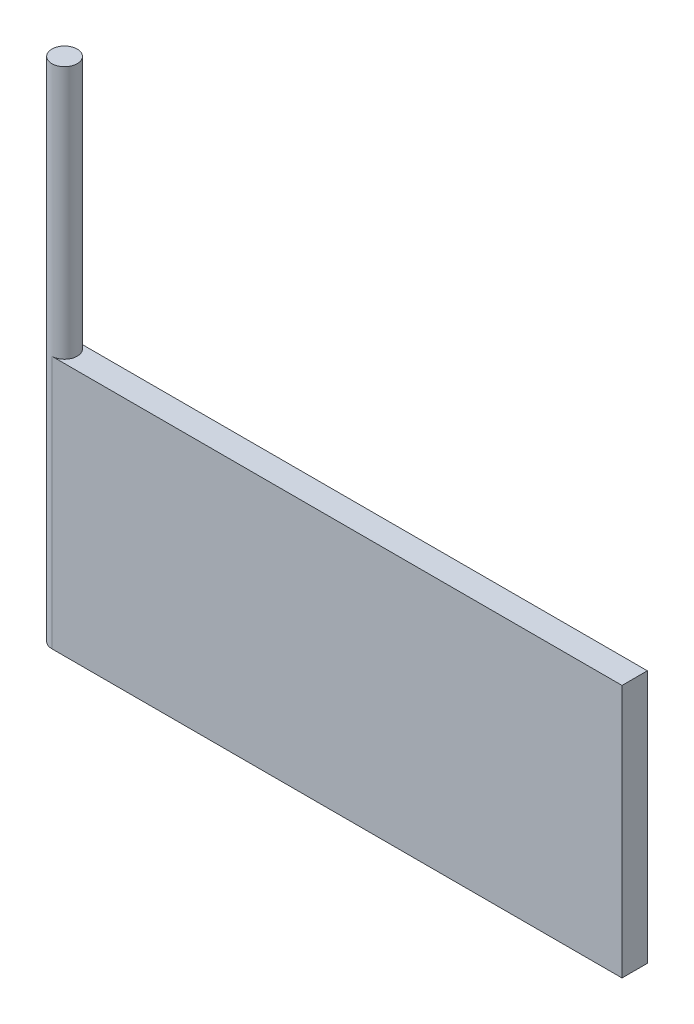
SolidWorks part; units mm, degrees
ref_plane "Front Plane" through (0, 0, 0) normal (0, 0, 1) x (1, 0, 0)
ref_plane "Top Plane" through (0, 0, 0) normal (0, 1, 0) x (1, 0, 0)
ref_plane "Right Plane" through (0, 0, 0) normal (1, 0, 0) x (0, 0, -1)
sketch "Sketch1" plane through (0, 0, 0) normal (0, 0, 1) x (1, 0, 0)
  line L0 (0, -55) -> (0, 55) construction
  line L1 (0, 20) -> (90, 20)
  line L2 (0, 20) -> (0, -20)
  line L3 (0, -20) -> (90, -20)
  line L4 (90, 20) -> (90, -20)
  dimension "D1" = 90
  dimension "D2" = 40
  dimension "D3" = 20
extrude "Boss-Extrude1" add sketch "Sketch1" against normal mid plane 4
sketch "Sketch3" plane through (0, 0, 0) normal (0, 1, 0) x (1, 0, 0)
  circle A0 centre (0, 0) radius 2
sketch "Sketch4" plane through (0, -20, 0) normal (0, -1, 0) x (1, 0, 0)
  circle A0 centre (0, 0) radius 2
extrude "Boss-Extrude2" add sketch "Sketch4" against normal blind 80
